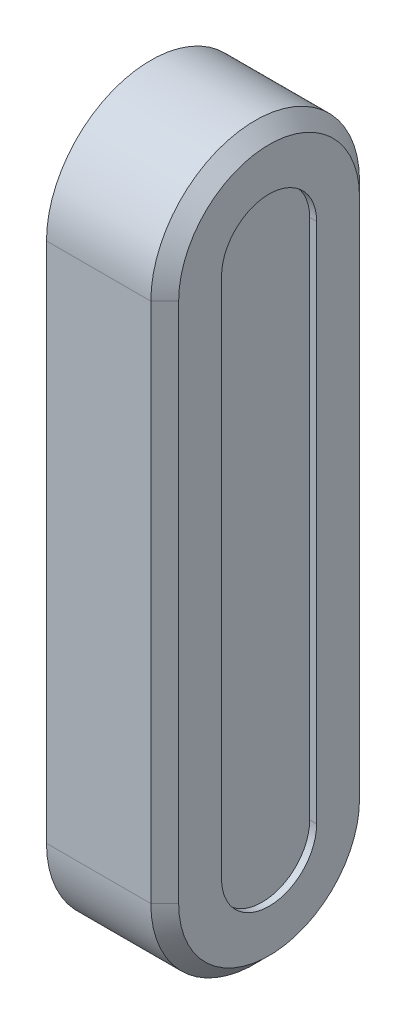
SolidWorks part; units mm, degrees
ref_plane "前视基准面" through (0, 0, 0) normal (0, 0, 1) x (1, 0, 0)
ref_plane "上视基准面" through (0, 0, 0) normal (0, 1, 0) x (1, 0, 0)
ref_plane "右视基准面" through (0, 0, 0) normal (1, 0, 0) x (0, 0, -1)
other "Configuration Table"
sketch "草图1" plane through (0, 0, 0) normal (1, 0, 0) x (0, 0, -1)
  circle A0 centre (0, 0) radius 4.9
  dimension "D1" = 9.8
extrude "凸台-拉伸1" add sketch "草图1" along normal blind 10
sketch "草图2" plane through (10, 0, 0) normal (1, 0, 0) x (0, 0, -1)
  line L0 (0, 0) -> (0, -75) construction
  line L1 (15, 0) -> (15, -75)
  line L2 (-15, 0) -> (-15, -75)
  arc A1 (15, 0) -> (-15, 0) centre (0, 0) ccw
  arc A2 (-15, -75) -> (15, -75) centre (0, -75) ccw
  point P3 (0, -37.5)
  dimension "D1" = 15
  dimension "D2" = 75
extrude "凸台-拉伸2" add sketch "草图2" along normal blind 20
sketch "草图3" plane through (10, 0, 0) normal (-1, 0, 0) x (0, 0, 1)
  circle A0 centre (0, -75) radius 5
extrude "凸台-拉伸3" add sketch "草图3" along normal blind 20
chamfer "倒角1" distance 2 angle 45 8 edges at (10, -37.5, -15) (30, -37.5, -15) (10, 15, 0) (30, 15, 0) (10, -90, 0) (30, -90, 0) (10, -37.5, 15) (30, -37.5, 15)
sketch "草图4" plane through (30, 0, 0) normal (1, 0, 0) x (0, 0, -1)
  line L0 (0, 0) -> (0, -75) construction
  line L1 (6.8356, 0) -> (6.8356, -75)
  line L2 (-6.8356, 0) -> (-6.8356, -75)
  arc A0 (6.8356, 0) -> (-6.8356, 0) centre (0, 0) ccw
  arc A1 (-6.8356, -75) -> (6.8356, -75) centre (0, -75) ccw
  point P4 (0, -37.5)
extrude "切除-拉伸1" cut sketch "草图4" against normal blind 1
sketch "草图5" plane through (-10, 0, 0) normal (-1, 0, 0) x (0, 0, 1)
  line L1 (-91.051, -205.5754) -> (21.1611, -205.5754)
  line L2 (-91.051, -205.5754) -> (-91.051, 15.9366)
  line L3 (-91.051, 15.9366) -> (21.1611, 15.9366)
  line L4 (21.1611, -205.5754) -> (21.1611, 15.9366)
  line L5 (-91.051, -205.5754) -> (21.1611, 15.9366) construction
  line L6 (-91.051, 15.9366) -> (21.1611, -205.5754) construction
  point P0 (-34.9449, -94.8194)
extrude "切除-拉伸2" cut sketch "草图5" against normal blind 23
sketch "草图6" plane through (13, 0, 0) normal (-1, 0, 0) x (0, 0, 1)
  line L0 (0, 0) -> (0, -75) construction
  line L1 (13, 0) -> (13, -75)
  line L2 (-13, 0) -> (-13, -75)
  line L3 (15, 0) -> (15, -75) construction
  arc A0 (13, 0) -> (-13, 0) centre (0, 0) ccw
  arc A1 (-13, -75) -> (13, -75) centre (0, -75) ccw
  point P4 (0, -37.5)
  dimension "D1" = 2
extrude "切除-拉伸3" cut sketch "草图6" against normal blind 14
sketch "草图7" plane through (27, 0, 0) normal (-1, 0, 0) x (0, 0, 1)
  line L0 (-13, -51.2353) -> (13, -51.2353)
  line L1 (-13, 0) -> (-13, -75) construction
  line L2 (13, -75) -> (13, 0) construction
